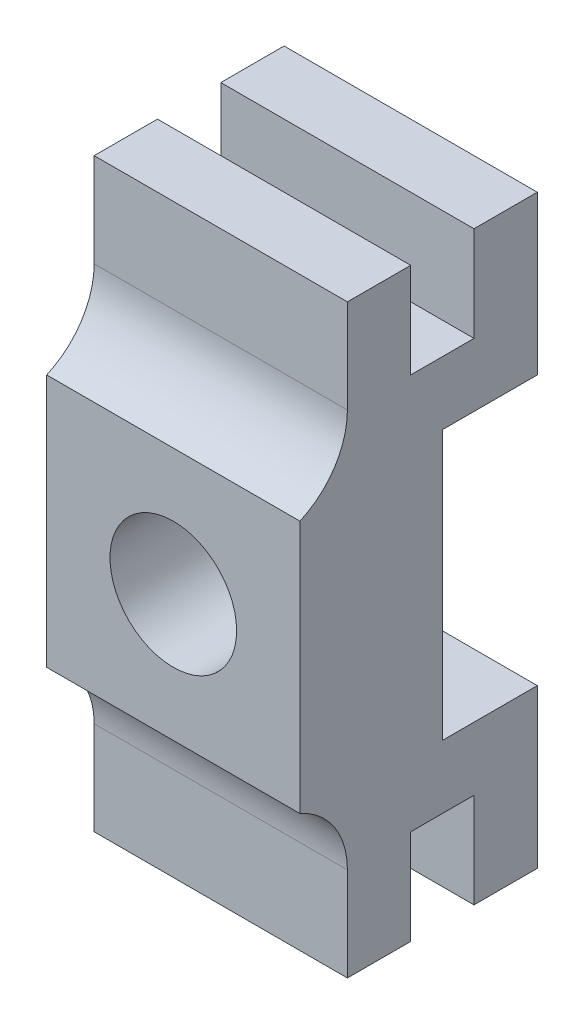
SolidWorks part; units mm, degrees
ref_plane "Front Plane" through (0, 0, 0) normal (1, 0, 0) x (0, 1, 0)
ref_plane "Top Plane" through (0, 0, 0) normal (0, 0, 1) x (0, 1, 0)
ref_plane "Right Plane" through (0, 0, 0) normal (0, 1, 0) x (-1, 0, 0)
sketch "Sketch1" plane through (0, 0, 0) normal (1, 0, 0) x (0, 1, 0)
  line L0 (0, 0) -> (0, 8937.7881) construction
  line L1 (0, 0) -> (8937.7881, 0) construction
  line L2 (8, 9) -> (-8, 9)
  line L3 (-12.5826, 6) -> (-18.5, 6)
  line L4 (-18.5, 6) -> (-18.5, 2)
  line L5 (-18.5, 2) -> (-12.5, 2)
  line L6 (-12.5, 2) -> (-12.5, -2)
  line L7 (-12.5, -2) -> (-18.5, -2)
  line L8 (-18.5, -2) -> (-18.5, -6)
  line L9 (-18.5, -6) -> (-8.5, -6)
  line L10 (-8.5, -6) -> (-8.5, 0)
  line L11 (-8.5, 0) -> (8.5, 0)
  line L12 (8.5, -6) -> (8.5, 0)
  line L13 (18.5, -6) -> (8.5, -6)
  line L14 (18.5, -2) -> (18.5, -6)
  line L15 (12.5, -2) -> (18.5, -2)
  line L16 (12.5, 2) -> (12.5, -2)
  line L17 (18.5, 2) -> (12.5, 2)
  line L18 (18.5, 6) -> (18.5, 2)
  line L19 (12.5826, 6) -> (18.5, 6)
  arc A2 (-8, 9) -> (-12.5826, 6) centre (-12.5826, 11) cw
  arc A3 (8, 9) -> (12.5826, 6) centre (12.5826, 11) ccw
  point P7 (0, 0)
  point P19 (0, 0)
  point P26 (0, 0)
  point P29 (0, 9)
  point P31 (0, 0)
  point P32 (0, 0)
  dimension "D2" = 15
  dimension "D9" = 5
  dimension "D1" = 16
  dimension "D3" = 37
  dimension "D4" = 12
  dimension "D5" = 6
  dimension "D6" = 4
  dimension "D7" = 10
  dimension "D8" = 6
extrude "Boss-Extrude1" add sketch "Sketch1" along normal mid plane 16
sketch "Sketch2" plane through (0, 0, 9) normal (0, 0, 1) x (1, 0, 0)
  circle A0 centre (0, 0) radius 4
  dimension "D1" = 8
extrude "Cut-Extrude1" cut sketch "Sketch2" against normal through all both and the other way through all
